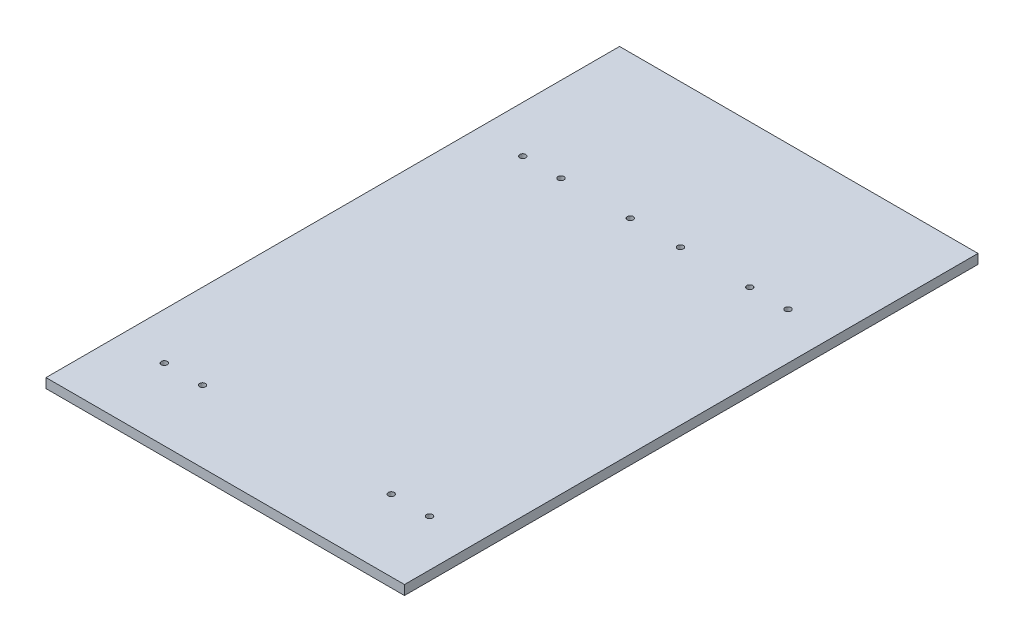
SolidWorks part; units mm, degrees
ref_plane "Front Plane" through (0, 0, 0) normal (0, 0, 1) x (1, 0, 0)
ref_plane "Top Plane" through (0, 0, 0) normal (0, 1, 0) x (1, 0, 0)
ref_plane "Right Plane" through (0, 0, 0) normal (1, 0, 0) x (0, 0, -1)
sketch "Sketch1" plane through (0, 0, 0) normal (0, 1, 0) x (1, 0, 0)
  line L0 (0, 240) -> (0, -240) construction
  line L1 (-150, -240) -> (150, -240)
  line L2 (-150, -240) -> (-150, 240)
  line L3 (-150, 240) -> (150, 240)
  line L4 (150, -240) -> (150, 240)
  line L5 (-150, -240) -> (150, 240) construction
  line L6 (-150, 240) -> (150, -240) construction
  line L7 (-95, 240) -> (-95, -240) construction
  line L8 (-111, 120) -> (-111, -180) construction
  circle A0 centre (-111, 120) radius 2.5
  circle A1 centre (-111, -180) radius 2.5
  circle A2 centre (-79, -180) radius 2.5
  circle A3 centre (-79, 120) radius 2.5
  circle A4 centre (79, -180) radius 2.5
  circle A5 centre (111, -180) radius 2.5
  circle A6 centre (79, 120) radius 2.5
  circle A7 centre (111, 120) radius 2.5
  circle A8 centre (-21, 120) radius 2.5
  circle A9 centre (21, 120) radius 2.5
  point P0 (0, 0)
  dimension "D4" = 5
  dimension "D5" = 16
  dimension "D6" = 120
  dimension "D8" = 5
  dimension "D9" = 21
  dimension "D10" = 120
  dimension "D1" = 300
  dimension "D2" = 480
  dimension "D3" = 95
  dimension "D7" = 300
extrude "Boss-Extrude1" add sketch "Sketch1" along normal blind 8
